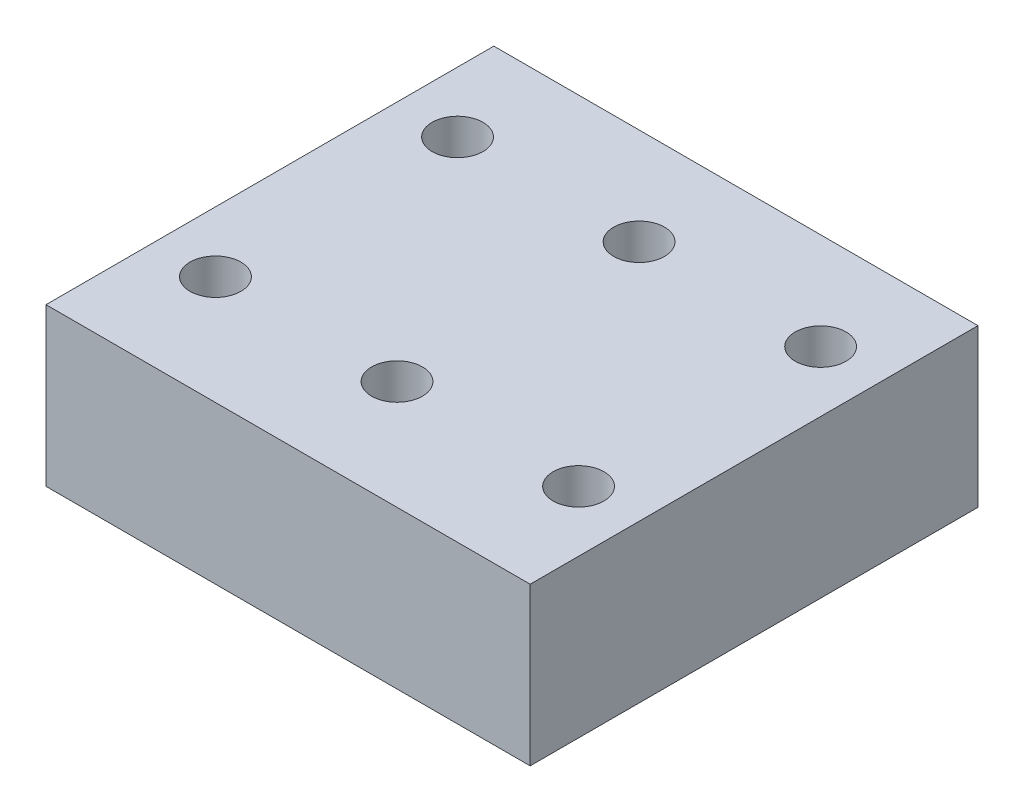
SolidWorks part; units mm, degrees
material "ABS"
ref_plane "前视基准面" through (0, 0, 0) normal (0, 0, 1) x (1, 0, 0)
ref_plane "上视基准面" through (0, 0, 0) normal (0, 1, 0) x (1, 0, 0)
ref_plane "右视基准面" through (0, 0, 0) normal (1, 0, 0) x (0, 0, -1)
other "Configuration Table"
sketch "草图1" plane through (0, 0, 0) normal (0, 1, 0) x (1, 0, 0)
  line L0 (20, 0) -> (20, -35.6979) construction
  line L1 (0, 0) -> (40, 0)
  line L2 (0, 0) -> (0, -37)
  line L3 (0, -37) -> (40, -37)
  line L4 (40, 0) -> (40, -37)
  circle A0 centre (20, -28) radius 2.1
  circle A1 centre (20, -8) radius 2.1
  circle A2 centre (35, -8) radius 2.1
  circle A3 centre (35, -28) radius 2.1
  circle A4 centre (5, -28) radius 2.1
  circle A5 centre (5, -8) radius 2.1
  dimension "D3" = 4.2
  dimension "D4" = 9
  dimension "D6" = 20
  dimension "D8" = 15
  dimension "D1" = 40
  dimension "D2" = 37
  dimension "D5" = 2
  dimension "D7" = 2
extrude "凸台-拉伸1" add sketch "草图1" along normal blind 13
